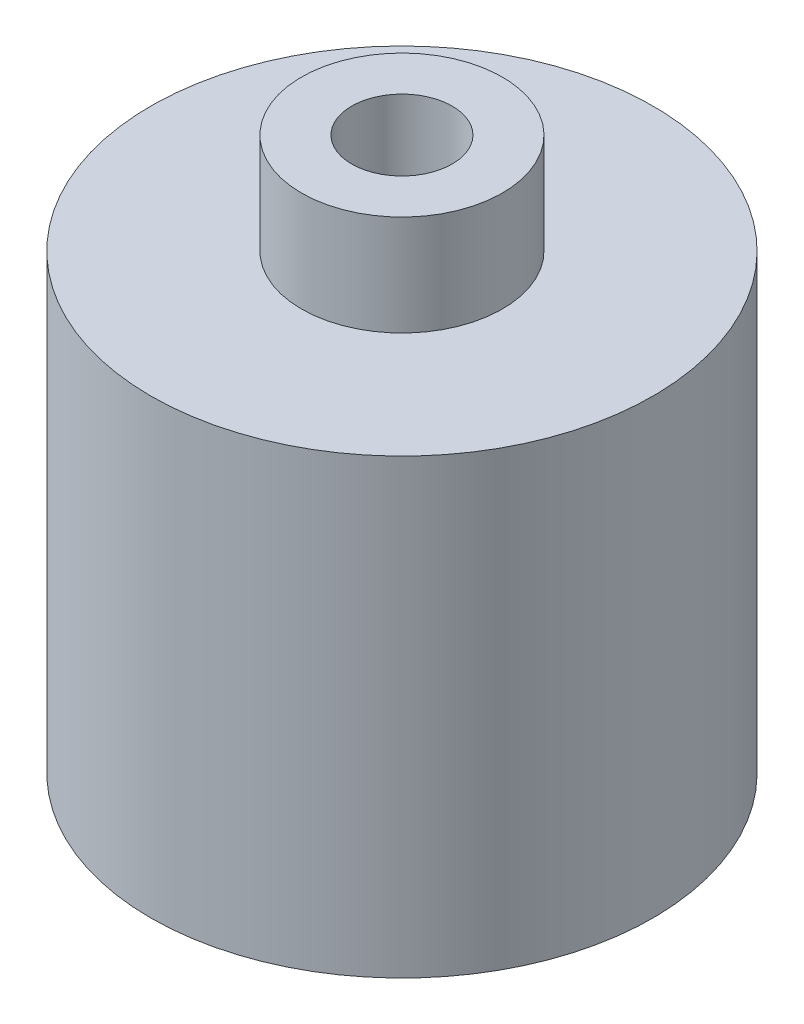
SolidWorks part; units mm, degrees
ref_plane "Front Plane" through (0, 0, 0) normal (0, 0, 1) x (1, 0, 0)
ref_plane "Top Plane" through (0, 0, 0) normal (0, 1, 0) x (1, 0, 0)
ref_plane "Right Plane" through (0, 0, 0) normal (1, 0, 0) x (0, 0, -1)
sketch "Sketch1" plane through (0, 0, 0) normal (0, 1, 0) x (1, 0, 0)
  circle A0 centre (0, 0) radius 15.875
  circle A1 centre (0, 0) radius 12.7
  dimension "D1" = 25.4
  dimension "D2" = 3.175
extrude "Boss-Extrude1" add sketch "Sketch1" along normal blind 25.4
sketch "Sketch2" plane through (0, 25.4, 0) normal (0, 1, 0) x (1, 0, 0)
  circle A0 centre (0, 0) radius 15.875
  circle A1 centre (0, 0) radius 15.875 construction
  circle A2 centre (0, 0) radius 3.175
  dimension "D1" = 6.35
extrude "Boss-Extrude2" add sketch "Sketch2" along normal blind 3.175
sketch "Sketch3" plane through (0, 28.575, 0) normal (0, 1, 0) x (1, 0, 0)
  circle A0 centre (0, 0) radius 3.175
  circle A1 centre (0, 0) radius 6.35
  circle A2 centre (0, 0) radius 3.175 construction
  dimension "D1" = 3.175
extrude "Boss-Extrude3" add sketch "Sketch3" along normal blind 6.35
